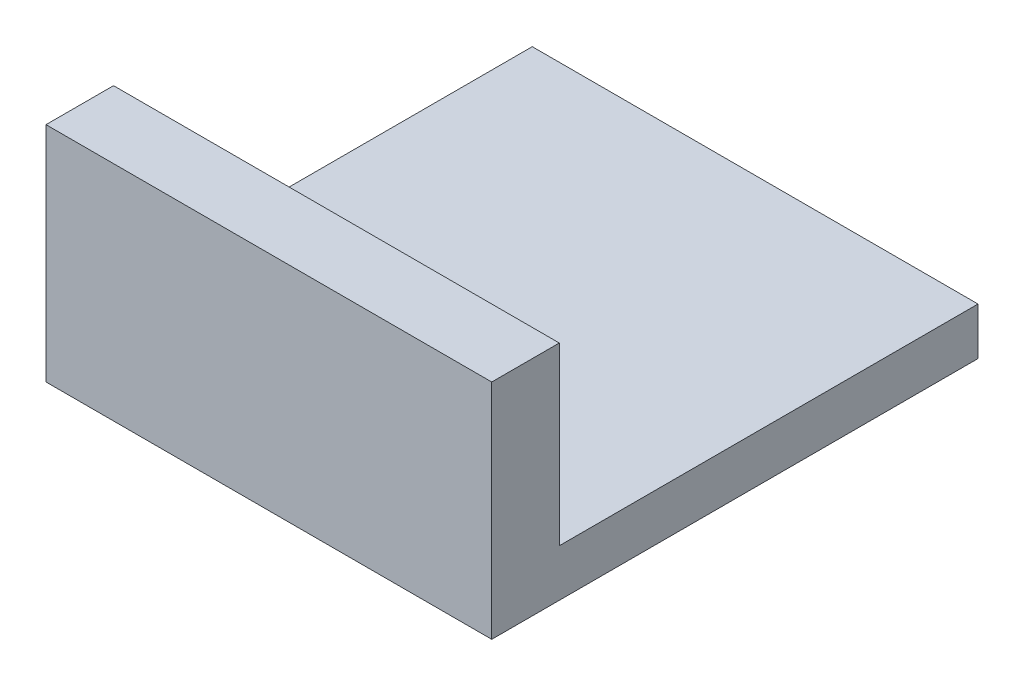
SolidWorks part; units mm, degrees
ref_plane "Front" through (0, 0, 0) normal (0, 0, 1) x (1, 0, 0)
ref_plane "Top" through (0, 0, 0) normal (0, 1, 0) x (1, 0, 0)
ref_plane "Right" through (0, 0, 0) normal (1, 0, 0) x (0, 0, -1)
sketch "Sketch1" plane through (0, 0, 0) normal (0, 1, 0) x (1, 0, 0)
  line L1 (-8.25, -9) -> (8.25, -9)
  line L2 (-8.25, -9) -> (-8.25, 9)
  line L3 (-8.25, 9) -> (8.25, 9)
  line L4 (8.25, -9) -> (8.25, 9)
  line L5 (-8.25, -9) -> (8.25, 9) construction
  line L6 (-8.25, 9) -> (8.25, -9) construction
  point P0 (0, 0)
  dimension "D1" = 16.5
  dimension "D2" = 18
extrude "Boss-Extrude1" add sketch "Sketch1" along normal blind 1.75
sketch "Sketch2" plane through (0, 0, 0) normal (0, 1, 0) x (1, 0, 0)
  line L0 (-8.25, -1) -> (8.25, -1) construction
  line L1 (-8.25, 9) -> (-8.25, -9) construction
  line L2 (8.25, -9) -> (8.25, 9) construction
  line L4 (-2, -3) -> (2, -3)
  line L5 (-2, -3) -> (-2, 1)
  line L6 (-2, 1) -> (2, 1)
  line L7 (2, -3) -> (2, 1)
  line L8 (-2, -3) -> (2, 1) construction
  line L9 (-2, 1) -> (2, -3) construction
  line L10 (8.25, 9) -> (-8.25, 9) construction
  point P6 (0, -1)
  dimension "D1" = 8
  dimension "D2" = 4
  dimension "D3" = 4
sketch "Sketch3" plane through (0, 1.75, 0) normal (0, 1, 0) x (1, 0, 0)
  line L0 (8.25, -9) -> (8.25, 9) construction
  line L1 (-8.25, -9) -> (8.25, -9)
  line L2 (-8.25, -9) -> (-8.25, -6.5)
  line L3 (-8.25, -6.5) -> (8.25, -6.5)
  line L4 (8.25, -9) -> (8.25, -6.5)
  dimension "D1" = 2.5
extrude "Boss-Extrude2" add sketch "Sketch3" along normal blind 6.5
extrude "Boss-Extrude3" add sketch "Sketch2" against normal blind 2
